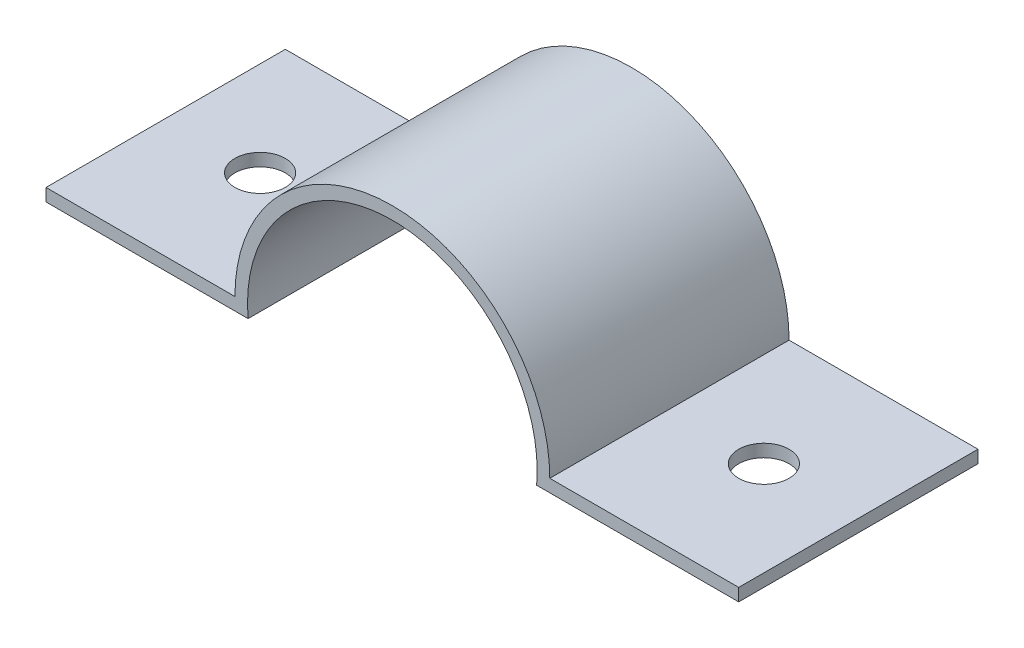
SolidWorks part; units mm, degrees
material "AISI 1020"
ref_plane "Ön Düzlem" through (0, 0, 0) normal (0, 0, 1) x (1, 0, 0)
ref_plane "Üst Düzlem" through (0, 0, 0) normal (0, 1, 0) x (1, 0, 0)
ref_plane "Sağ Düzlem" through (0, 0, 0) normal (1, 0, 0) x (0, 0, -1)
sketch "Çizim1" plane through (0, 0, 0) normal (0, 0, 1) x (1, 0, 0)
  line L0 (0, 0) -> (15, 0)
  line L2 (40, 0) -> (55, 0)
  line L3 (0, 0) -> (0, -1)
  line L4 (0, -1) -> (16, -1)
  line L5 (16, -1) -> (16.0436, -1)
  line L6 (38.9564, -1) -> (55, -1)
  line L7 (55, -1) -> (55, 0)
  arc A0 (40, 0) -> (15, 0) centre (27.5, 0) ccw
  arc A1 (38.9564, -1) -> (16.0436, -1) centre (27.5, 0) ccw
  point P3 (27.5, 0)
  point P5 (27.5, -1)
  dimension "D3" = 1
  dimension "D5" = 23
  dimension "D1" = 15
  dimension "D2" = 15
  dimension "D4" = 16
extrude "Yükseklik-Ekstrüzyon1" add sketch "Çizim1" along normal blind 19
sketch "Çizim2" plane through (0, 0, 0) normal (0, 1, 0) x (1, 0, 0)
  line L0 (0, -9.5) -> (55, -9.5) construction
  line L1 (0, -19) -> (0, 0) construction
  line L2 (55, -19) -> (55, 0) construction
  circle A0 centre (7.5, -9.5) radius 2
  circle A1 centre (47.5, -9.5) radius 2
  dimension "D1" = 4
  dimension "D2" = 4
extrude "Kes-Ekstrüzyon1" cut sketch "Çizim2" against normal blind 19
